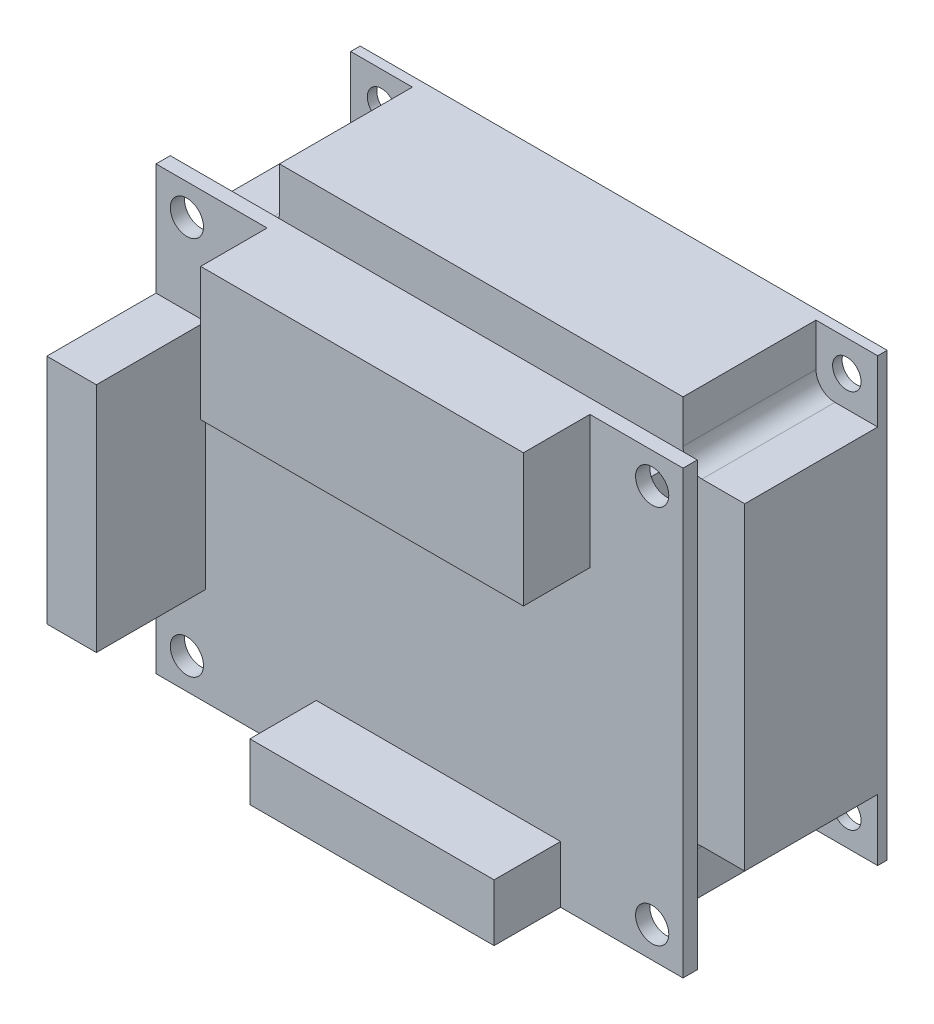
SolidWorks part; units mm, degrees
ref_plane "前视基准面" through (0, 0, 0) normal (0, 0, 1) x (1, 0, 0)
ref_plane "上视基准面" through (0, 0, 0) normal (0, 1, 0) x (1, 0, 0)
ref_plane "右视基准面" through (0, 0, 0) normal (1, 0, 0) x (0, 0, -1)
sketch "草图1" plane through (0, 0, 0) normal (0, 0, 1) x (1, 0, 0)
  line L1 (-27.75, -23.25) -> (27.75, -23.25)
  line L2 (-27.75, -23.25) -> (-27.75, 23.25)
  line L3 (-27.75, 23.25) -> (27.75, 23.25)
  line L4 (27.75, -23.25) -> (27.75, 23.25)
  line L5 (-27.75, -23.25) -> (27.75, 23.25) construction
  line L6 (-27.75, 23.25) -> (27.75, -23.25) construction
  point P0 (0, 0)
  dimension "D1" = 46.5
  dimension "D2" = 55.5
extrude "凸台-拉伸1" add sketch "草图1" along normal blind 15
sketch "草图2" plane through (0, 0, 15) normal (0, 0, 1) x (1, 0, 0)
  line L1 (-27.75, 23.25) -> (-21.25, 23.25)
  line L2 (-27.75, 23.25) -> (-27.75, 16.75)
  line L3 (-27.75, 16.75) -> (-21.25, 16.75)
  line L4 (-21.25, 23.25) -> (-21.25, 16.75)
  line L5 (27.75, 23.25) -> (21.25, 23.25)
  line L6 (27.75, 23.25) -> (27.75, 16.75)
  line L7 (27.75, 16.75) -> (21.25, 16.75)
  line L8 (21.25, 23.25) -> (21.25, 16.75)
  line L9 (27.75, -23.25) -> (21.25, -23.25)
  line L10 (27.75, -23.25) -> (27.75, -16.75)
  line L11 (27.75, -16.75) -> (21.25, -16.75)
  line L12 (21.25, -23.25) -> (21.25, -16.75)
  line L13 (-27.75, -23.25) -> (-21.25, -23.25)
  line L14 (-27.75, -23.25) -> (-27.75, -16.75)
  line L15 (-27.75, -16.75) -> (-21.25, -16.75)
  line L16 (-21.25, -23.25) -> (-21.25, -16.75)
  dimension "D1" = 6.5
  dimension "D2" = 6.5
  dimension "D3" = 6.5
  dimension "D4" = 6.5
extrude "切除-拉伸1" cut sketch "草图2" against normal blind 14
fillet "圆角1" radius 2 4 edges at (-21.25, -16.75, 8) (21.25, -16.75, 8) (21.25, 16.75, 8) (-21.25, 16.75, 8)
sketch "草图3" plane through (0, 0, 15) normal (0, 0, 1) x (1, 0, 0)
  line L0 (27.75, -16.75) -> (27.75, 16.75) construction
  line L1 (-20.75, 17.1471) -> (-16.75, 17.1471)
  line L2 (-20.75, 17.1471) -> (-20.75, -16.8529)
  line L3 (-20.75, -16.8529) -> (-16.75, -16.8529)
  line L4 (-16.75, 17.1471) -> (-16.75, -16.8529)
  line L5 (16.75, 17.1471) -> (20.75, 17.1471)
  line L6 (16.75, 17.1471) -> (16.75, -16.8529)
  line L7 (16.75, -16.8529) -> (20.75, -16.8529)
  line L8 (20.75, 17.1471) -> (20.75, -16.8529)
  line L9 (-27.75, 16.75) -> (-27.75, -16.75) construction
  dimension "D1" = 34
  dimension "D2" = 4
  dimension "D3" = 34
  dimension "D4" = 4
  dimension "D5" = 7
  dimension "D6" = 7
extrude "凸台-拉伸2" add sketch "草图3" along normal blind 5
sketch "草图4" plane through (0, 0, 20) normal (0, 0, 1) x (1, 0, 0)
  line L1 (-27.75, 23.25) -> (27.75, 23.25)
  line L2 (-27.75, 23.25) -> (-27.75, -23.25)
  line L3 (-27.75, -23.25) -> (27.75, -23.25)
  line L4 (27.75, 23.25) -> (27.75, -23.25)
extrude "凸台-拉伸3" add sketch "草图4" along normal blind 1.5
sketch "草图5" plane through (0, 0, 1) normal (0, 0, 1) x (1, 0, 0)
  line L3 (24.5, -20) -> (-24.5, -20) construction
  line L6 (24.5, -20) -> (24.5, 20) construction
  line L7 (24.5, 20) -> (-24.5, 20) construction
  line L8 (-24.5, -20) -> (-24.5, 20) construction
  line L9 (24.5, -20) -> (-24.5, 20) construction
  line L10 (24.5, 20) -> (-24.5, -20) construction
  circle A0 centre (24.5, 20) radius 1.5
  circle A1 centre (-24.5, 20) radius 1.5
  circle A2 centre (-24.5, -20) radius 1.5
  circle A3 centre (24.5, -20) radius 1.5
  point P0 (0, 0)
  dimension "D1" = 40
  dimension "D3" = 3
  dimension "D4" = 3
  dimension "D5" = 3
  dimension "D6" = 3
  dimension "D2" = 49
extrude "切除-拉伸2" cut sketch "草图5" against normal blind 1
sketch "草图6" plane through (0, 0, 21.5) normal (0, 0, 1) x (1, 0, 0)
  line L1 (-24.5, -20) -> (24.5, -20) construction
  line L2 (-24.5, -20) -> (-24.5, 20) construction
  line L3 (-24.5, 20) -> (24.5, 20) construction
  line L4 (24.5, -20) -> (24.5, 20) construction
  line L5 (-24.5, -20) -> (24.5, 20) construction
  line L6 (-24.5, 20) -> (24.5, -20) construction
  circle A0 centre (-24.5, 20) radius 1.75
  circle A1 centre (24.5, 20) radius 1.75
  circle A2 centre (24.5, -20) radius 1.75
  circle A3 centre (-24.5, -20) radius 1.75
  point P0 (0, 0)
  dimension "D3" = 3.5
  dimension "D4" = 3.5
  dimension "D5" = 3.5
  dimension "D6" = 3.5
  dimension "D1" = 40
  dimension "D2" = 49
extrude "切除-拉伸3" cut sketch "草图6" against normal blind 2
sketch "草图7" plane through (0, 0, 21.5) normal (0, 0, 1) x (1, 0, 0)
  line L0 (27.75, 23.25) -> (-27.75, 23.25) construction
  line L1 (-16.0505, 23.25) -> (17.9447, 23.25)
  line L2 (-16.0505, 23.25) -> (-16.0505, 9.2714)
  line L3 (-16.0505, 9.2714) -> (17.9447, 9.2714)
  line L4 (17.9447, 23.25) -> (17.9447, 9.2714)
  line L5 (-27.75, 23.25) -> (-27.75, -23.25) construction
  line L6 (-27.75, 11.4646) -> (-22.5305, 11.4646)
  line L7 (-27.75, 11.4646) -> (-27.75, -12.96)
  line L8 (-27.75, -12.96) -> (-22.5305, -12.96)
  line L9 (-22.5305, 11.4646) -> (-22.5305, -12.96)
  line L10 (-27.75, -23.25) -> (27.75, -23.25) construction
  line L11 (-10.8665, -17.2468) -> (14.8542, -17.2468)
  line L12 (-10.8665, -17.2468) -> (-10.8665, -23.25)
  line L13 (-10.8665, -23.25) -> (14.8542, -23.25)
  line L14 (14.8542, -17.2468) -> (14.8542, -23.25)
extrude "凸台-拉伸4" add sketch "草图7" along normal blind 10
sketch "草图8" plane through (0, 0, 31.5) normal (0, 0, 1) x (1, 0, 0)
  line L4 (-16.0505, 23.25) -> (-16.0505, 9.2714)
  line L5 (-16.0505, 9.2714) -> (17.9447, 9.2714)
  line L6 (17.9447, 9.2714) -> (17.9447, 23.25)
  line L7 (17.9447, 23.25) -> (-16.0505, 23.25)
  line L8 (-16.0505, 23.25) -> (-16.0505, 9.2714)
  line L9 (-16.0505, 9.2714) -> (17.9447, 9.2714)
  line L10 (17.9447, 9.2714) -> (17.9447, 23.25)
  line L11 (17.9447, 23.25) -> (-16.0505, 23.25)
  line L12 (-10.8665, -17.2468) -> (-10.8665, -23.25)
  line L13 (-10.8665, -23.25) -> (14.8542, -23.25)
  line L14 (14.8542, -23.25) -> (14.8542, -17.2468)
  line L15 (14.8542, -17.2468) -> (-10.8665, -17.2468)
  line L16 (-10.8665, -17.2468) -> (-10.8665, -23.25)
  line L17 (-10.8665, -23.25) -> (14.8542, -23.25)
  line L18 (14.8542, -23.25) -> (14.8542, -17.2468)
  line L19 (14.8542, -17.2468) -> (-10.8665, -17.2468)
  dimension "D1" = 0
  dimension "D2" = 0
extrude "切除-拉伸4" cut sketch "草图8" against normal blind 3
sketch "草图10" plane through (0, 0, 31.5) normal (0, 0, 1) x (1, 0, 0)
  line L4 (-27.75, 11.4646) -> (-27.75, -12.96)
  line L5 (-27.75, -12.96) -> (-22.5305, -12.96)
  line L6 (-27.75, -12.96) -> (-22.5305, -12.96)
  line L7 (-22.5305, -12.96) -> (-22.5305, 11.4646)
  line L8 (-27.75, 11.4646) -> (-27.75, -12.96)
  line L13 (-22.5305, 11.4646) -> (-27.75, 11.4646)
  line L14 (-22.5305, 11.4646) -> (-27.75, 11.4646)
  line L15 (-22.5305, -12.96) -> (-22.5305, 11.4646)
  dimension "D1" = 0
extrude "凸台-拉伸6" add sketch "草图10" along normal blind 1.5
